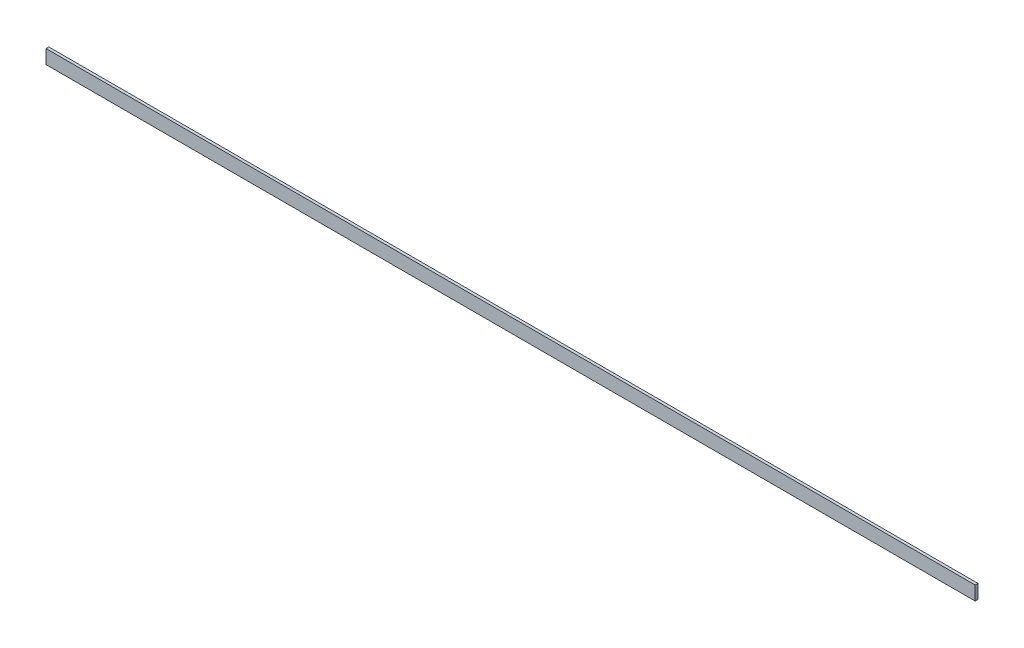
SolidWorks part; units mm, degrees
ref_plane "Front Plane" through (0, 0, 0) normal (0, 0, 1) x (1, 0, 0)
ref_plane "Top Plane" through (0, 0, 0) normal (0, 1, 0) x (1, 0, 0)
ref_plane "Right Plane" through (0, 0, 0) normal (1, 0, 0) x (0, 0, -1)
sketch "Sketch1" plane through (0, 0, 0) normal (0, 0, 1) x (1, 0, 0)
  line L2 (1000, 15) -> (0, 15)
  line L3 (0, 15) -> (0, 0)
  line L4 (1000, 15) -> (1000, 0)
  line L5 (0, 0) -> (1000, 0)
  dimension "D1" = 1000
  dimension "D2" = 15
extrude "Boss-Extrude1" add sketch "Sketch1" along normal blind 3 contours L2 L3 L5 L4
